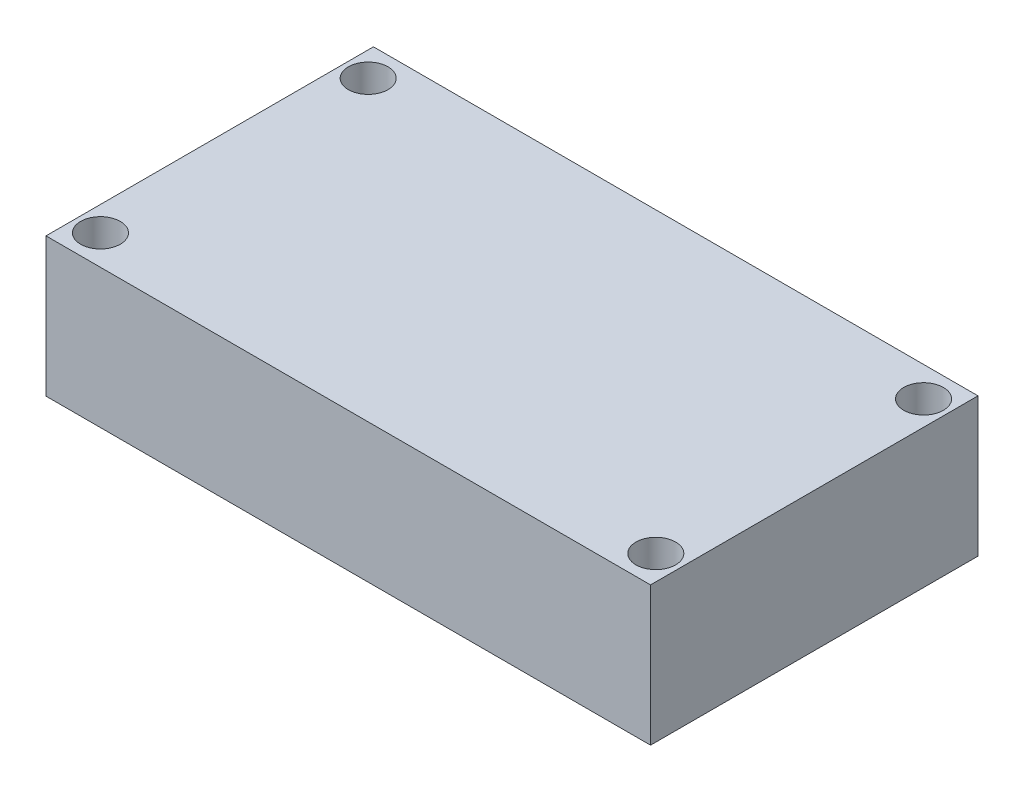
SolidWorks part; units mm, degrees
ref_plane "Plan de face" through (0, 0, 0) normal (0, 0, 1) x (1, 0, 0)
ref_plane "Plan de dessus" through (0, 0, 0) normal (0, 1, 0) x (1, 0, 0)
ref_plane "Plan de droite" through (0, 0, 0) normal (1, 0, 0) x (0, 0, -1)
sketch "Esquisse1" plane through (0, 0, 0) normal (0, 1, 0) x (1, 0, 0)
  line L1 (-30.48, -16.51) -> (30.48, -16.51)
  line L2 (-30.48, -16.51) -> (-30.48, 16.51)
  line L3 (-30.48, 16.51) -> (30.48, 16.51)
  line L4 (30.48, -16.51) -> (30.48, 16.51)
  line L5 (-30.48, -16.51) -> (30.48, 16.51) construction
  line L6 (-30.48, 16.51) -> (30.48, -16.51) construction
  point P0 (0, 0)
  dimension "D1" = 60.96
  dimension "D2" = 33.02
extrude "Boss.-Extru.1" add sketch "Esquisse1" along normal blind 14
sketch "Esquisse2" plane through (0, 14, 0) normal (0, 1, 0) x (1, 0, 0)
  line L0 (-28, 13.5) -> (28, 13.5) construction
  line L1 (0, 13.5) -> (0, 0) construction
  line L2 (0, 0) -> (-12.1282, 0) construction
  line L3 (-28, -13.5) -> (28, -13.5) construction
  line L4 (0, 0) -> (0, -13.5) construction
  circle A0 centre (-28, 13.5) radius 2
  circle A1 centre (28, 13.5) radius 2
  circle A2 centre (28, -13.5) radius 2
  circle A3 centre (-28, -13.5) radius 2
  dimension "D2" = 4
  dimension "D1" = 56
  dimension "D3" = 27
extrude "Enlèv. mat.-Extru.1" cut sketch "Esquisse2" against normal up to next
